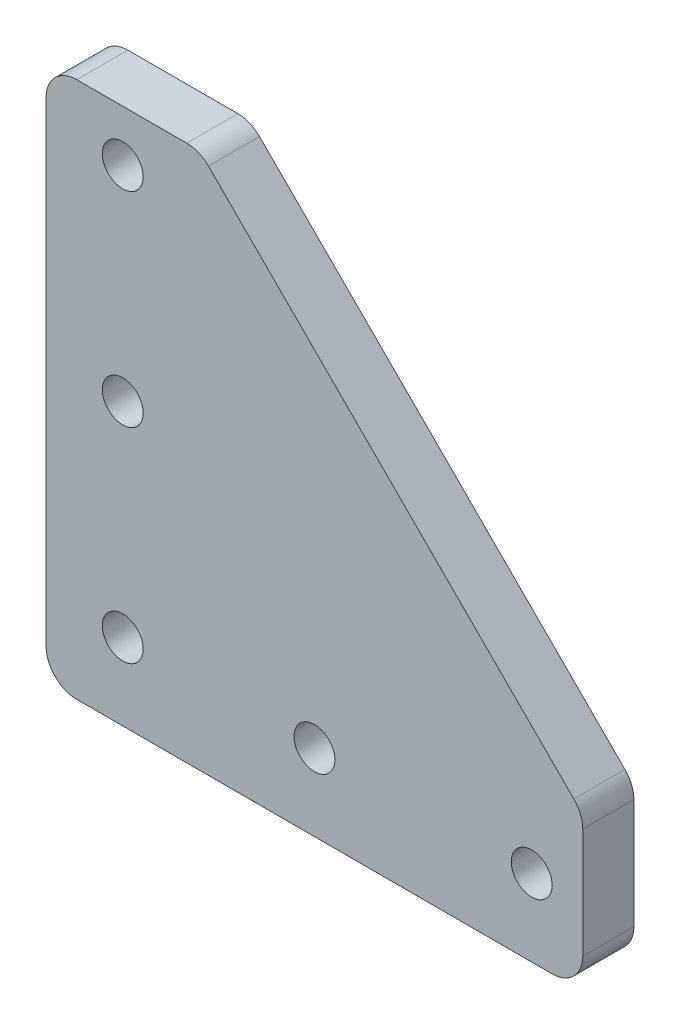
SolidWorks part; units mm, degrees
material "ﾎﾟﾘ塩化ﾋﾞﾆﾙ(PVC)硬質"
ref_plane "正面" through (0, 0, 0) normal (0, 0, 1) x (1, 0, 0)
ref_plane "平面" through (0, 0, 0) normal (0, 1, 0) x (1, 0, 0)
ref_plane "右側面" through (0, 0, 0) normal (1, 0, 0) x (0, 0, -1)
sketch "ｽｹｯﾁ1" plane through (0, 0, 0) normal (0, 0, 1) x (1, 0, 0)
  line L0 (15, 52.5) -> (52.5, 15)
  line L1 (0, 0) -> (52.5, 0)
  line L2 (0, 0) -> (0, 52.5)
  line L3 (0, 52.5) -> (52.5, 52.5)
  line L4 (52.5, 0) -> (52.5, 52.5)
  line L5 (0, 7.5) -> (52.5, 7.5) construction
  line L6 (7.5, 0) -> (7.5, 52.5) construction
  circle A0 centre (7.5, 7.5) radius 2
  circle A1 centre (7.5, 47.5) radius 2
  circle A2 centre (47.5, 7.5) radius 2
  circle A3 centre (7.5, 27.5) radius 2
  circle A4 centre (26.25, 7.5) radius 2
  dimension "D7" = 4
  dimension "D8" = 5
  dimension "D9" = 5
  dimension "D10" = 20
  dimension "D11" = 4
  dimension "D3" = 40
  dimension "D4" = 20
  dimension "D1" = 15
  dimension "D2" = 15
  dimension "D5" = 7.5
  dimension "D6" = 7.5
extrude "ﾎﾞｽ - 押し出し1" add sketch "ｽｹｯﾁ1" along normal blind 5 contours L1 L4 L0 L3 L2 A2 A1 A0
fillet "ﾌｨﾚｯﾄ1" radius 3 5 edges at (0, 0, 2.5) (52.5, 0, 2.5) (52.5, 15, 2.5) (15, 52.5, 2.5) (0, 52.5, 2.5)
